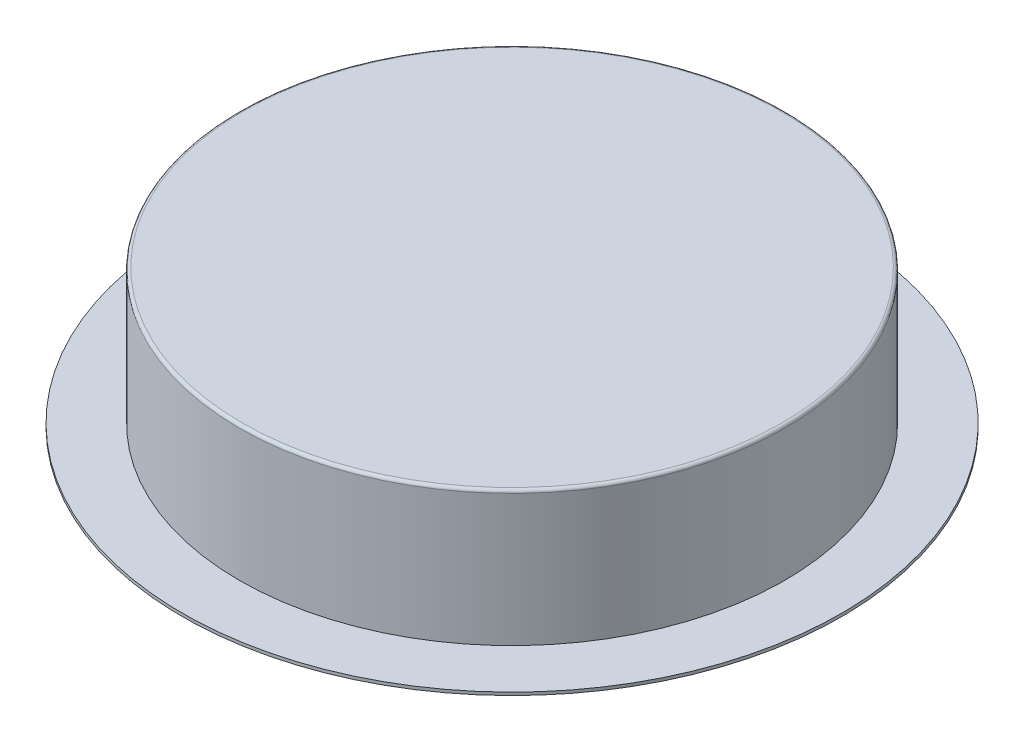
SolidWorks part; units mm, degrees
ref_plane "Спереди" through (0, 0, 0) normal (0, 0, 1) x (1, 0, 0)
ref_plane "Сверху" through (0, 0, 0) normal (0, 1, 0) x (1, 0, 0)
ref_plane "Справа" through (0, 0, 0) normal (1, 0, 0) x (0, 0, -1)
sketch "Эскиз1" plane through (0, 0, 0) normal (0, 1, 0) x (1, 0, 0)
  circle A0 centre (0, 0) radius 45
  circle A1 centre (0, 0) radius 45.5
extrude "Вытянуть1" add sketch "Эскиз1" along normal blind 22
sketch "Эскиз2" plane through (0, 0, 0) normal (0, -1, 0) x (1, 0, 0)
  circle A0 centre (0, 0) radius 45
  circle A1 centre (0, 0) radius 55
extrude "Вытянуть2" add sketch "Эскиз2" along normal blind 0.5 separate body
sketch "Эскиз3" plane through (0, 22, 0) normal (0, 1, 0) x (1, 0, 0)
  circle A0 centre (0, 0) radius 45.5
extrude "Вытянуть3" add sketch "Эскиз3" along normal blind 0.5
fillet "Скругление2" radius 0.5 1 edges at (0, 22.5, 45.5)
